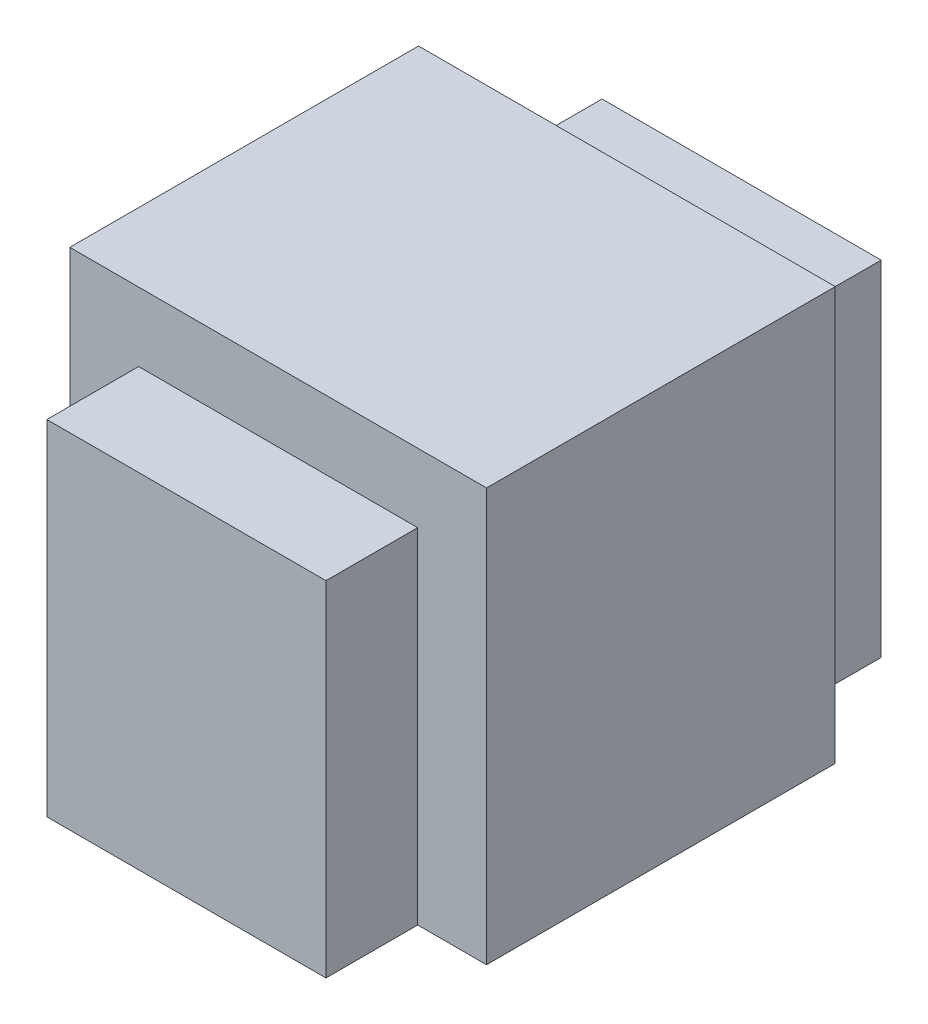
SolidWorks part; units mm, degrees
material "6061 Alloy"
ref_plane "Front Plane" through (0, 0, 0) normal (0, 0, 1) x (1, 0, 0)
ref_plane "Top Plane" through (0, 0, 0) normal (0, 1, 0) x (1, 0, 0)
ref_plane "Right Plane" through (0, 0, 0) normal (1, 0, 0) x (0, 0, -1)
sketch "Sketch1" plane through (0, 0, 0) normal (0, 0, 1) x (1, 0, 0)
  line L1 (0, 0) -> (90.825, 0)
  line L2 (0, 0) -> (0, 90)
  line L3 (0, 90) -> (90.825, 90)
  line L4 (90.825, 0) -> (90.825, 90)
  dimension "D1" = 90
  dimension "D2" = 90.825
extrude "Boss-Extrude1" add sketch "Sketch1" along normal blind 76
sketch "Sketch2" plane through (0, 0, 76) normal (0, 0, 1) x (1, 0, 0)
  line L0 (0, 0) -> (90.825, 0) construction
  line L1 (15, 0) -> (75.825, 0)
  line L2 (15, 0) -> (15, 75)
  line L3 (15, 75) -> (75.825, 75)
  line L4 (75.825, 0) -> (75.825, 75)
  line L5 (90.825, 90) -> (0, 90) construction
  line L6 (90.825, 0) -> (90.825, 90) construction
  line L7 (0, 90) -> (0, 0) construction
  dimension "D1" = 15
  dimension "D2" = 15
  dimension "D3" = 15
extrude "Boss-Extrude2" add sketch "Sketch2" along normal blind 20
sketch "Sketch3" plane through (0, 0, 0) normal (0, 0, -1) x (-1, 0, 0)
  line L4 (-15, 0) -> (-15, 75)
  line L5 (-75.825, 0) -> (-15, 0)
  line L6 (-75.825, 75) -> (-75.825, 0)
  line L7 (-15, 75) -> (-75.825, 75)
  line L12 (-15, 0) -> (-15, 75)
  line L13 (-75.825, 0) -> (-15, 0)
  line L14 (-75.825, 75) -> (-75.825, 0)
  line L15 (-15, 75) -> (-75.825, 75)
  dimension "D1" = 0
extrude "Boss-Extrude3" add sketch "Sketch3" along normal blind 25
